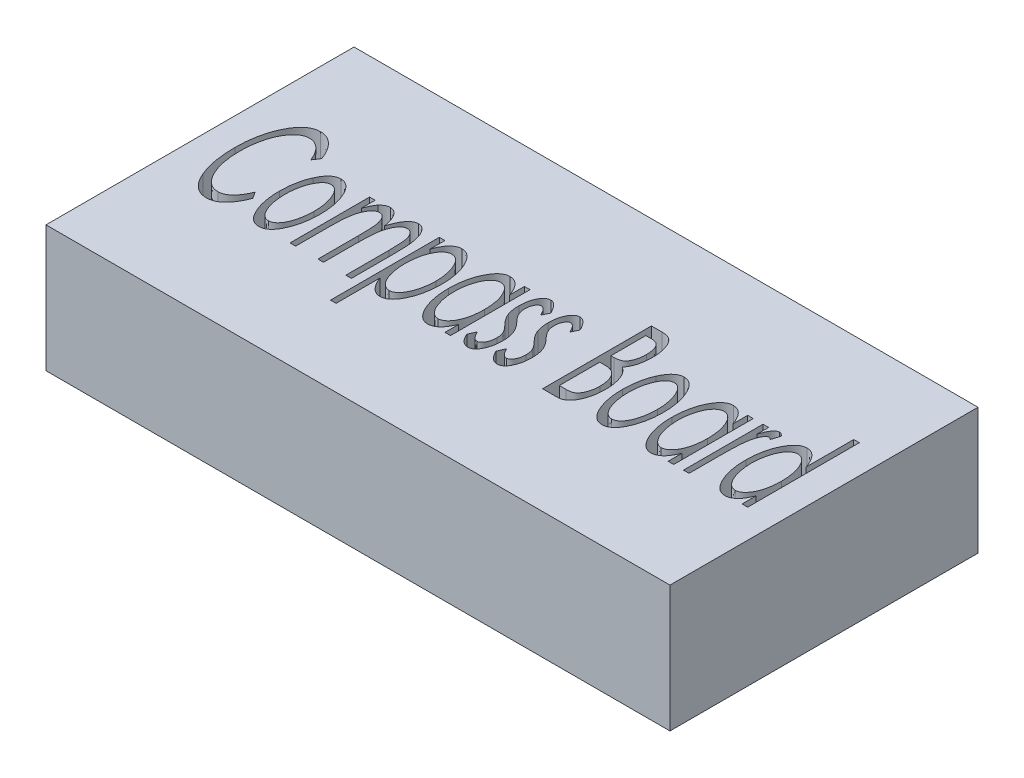
SolidWorks part; units mm, degrees
ref_plane "Front Plane" through (0, 0, 0) normal (0, 0, 1) x (1, 0, 0)
ref_plane "Top Plane" through (0, 0, 0) normal (0, 1, 0) x (1, 0, 0)
ref_plane "Right Plane" through (0, 0, 0) normal (1, 0, 0) x (0, 0, -1)
sketch "Sketch1" plane through (0, 0, 0) normal (0, 1, 0) x (1, 0, 0)
  line L1 (-10.033, -4.953) -> (10.033, -4.953)
  line L2 (-10.033, -4.953) -> (-10.033, 4.953)
  line L3 (-10.033, 4.953) -> (10.033, 4.953)
  line L4 (10.033, -4.953) -> (10.033, 4.953)
  line L5 (-10.033, -4.953) -> (10.033, 4.953) construction
  line L6 (-10.033, 4.953) -> (10.033, -4.953) construction
  point P0 (0, 0)
extrude "Boss-Extrude1" add sketch "Sketch1" along normal blind 4.064
sketch "Sketch2" plane through (0, 4.064, 0) normal (0, 1, 0) x (1, 0, 0)
  text T0 "Compass Board" font "Century Gothic" height 3.5
extrude "Cut-Extrude1" cut sketch "Sketch2" against normal blind 2.032
